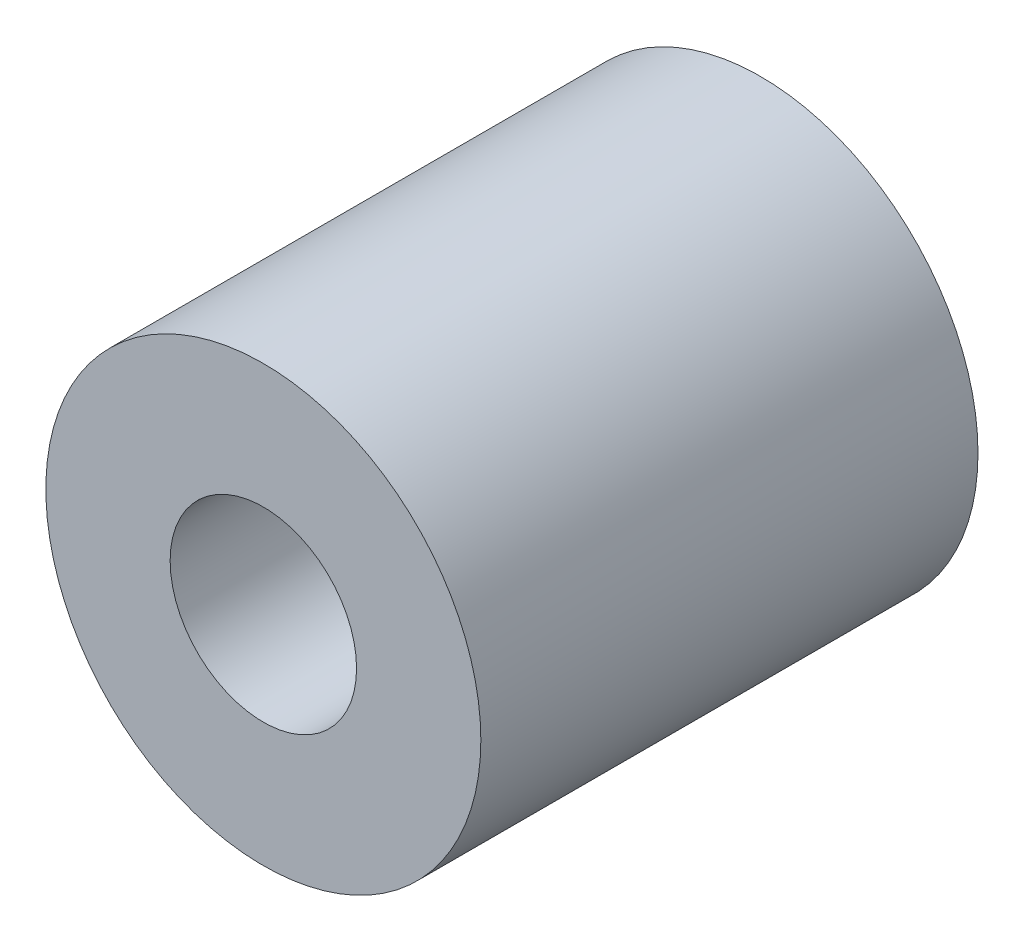
SolidWorks part; units mm, degrees
ref_plane "Front" through (0, 0, 0) normal (0, 0, 1) x (1, 0, 0)
ref_plane "Top" through (0, 0, 0) normal (0, 1, 0) x (1, 0, 0)
ref_plane "Right" through (0, 0, 0) normal (1, 0, 0) x (0, 0, -1)
sketch "Sketch1" plane through (0, 0, 0) normal (0, 0, 1) x (1, 0, 0)
  circle A0 centre (0, 0) radius 3.5
  circle A1 centre (0, 0) radius 1.5
  dimension "D1" = 7
  dimension "D2" = 3
extrude "Boss-Extrude1" add sketch "Sketch1" along normal blind 8
